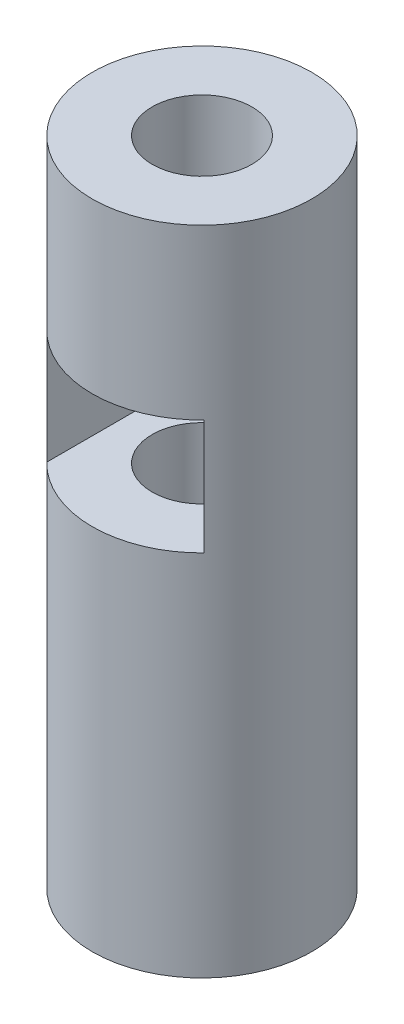
SolidWorks part; units mm, degrees
ref_plane "Front Plane" through (0, 0, 0) normal (0, 0, 1) x (1, 0, 0)
ref_plane "Top Plane" through (0, 0, 0) normal (0, 1, 0) x (1, 0, 0)
ref_plane "Right Plane" through (0, 0, 0) normal (1, 0, 0) x (0, 0, -1)
sketch "Sketch1" plane through (0, 0, 0) normal (0, 1, 0) x (1, 0, 0)
  circle A0 centre (0, 0) radius 3
  circle A1 centre (0, 0) radius 5.725
  dimension "D1" = 6
  dimension "D2" = 11.45
extrude "Boss-Extrude1" add sketch "Sketch1" along normal blind 34
ref_plane "Plane1" through (0, 7.2, 0) normal (0, 1, 0) x (1, 0, 0)
sketch "Sketch2" plane through (0, 0, 0) normal (0, -1, 0) x (-1, 0, 0)
  circle A0 centre (0, 0) radius 5.725
  dimension "D1" = 11.45
extrude "Boss-Extrude2" add sketch "Sketch2" against normal blind 34
sketch "Sketch3" plane through (0, 0, 0) normal (0, -1, 0) x (-1, 0, 0)
  circle A1 centre (0, 0) radius 2.6
  dimension "D1" = 5.2
extrude "Cut-Extrude1" cut sketch "Sketch3" against normal blind 40
sketch "Sketch4" plane through (0, 7.2, 0) normal (0, 1, 0) x (1, 0, 0)
  line L1 (0, -4.7343) -> (4.1, -2.3671)
  line L2 (4.1, -2.3671) -> (4.1, 2.3671)
  line L3 (4.1, 2.3671) -> (0, 4.7343)
  line L4 (0, 4.7343) -> (-4.1, 2.3671)
  line L5 (-4.1, 2.3671) -> (-4.1, -2.3671)
  line L6 (-4.1, -2.3671) -> (0, -4.7343)
  circle A0 centre (0, 0) radius 4.1 construction
  dimension "D1" = 8.2
extrude "Cut-Extrude2" cut sketch "Sketch4" against normal blind 4.7
sketch "Sketch5" plane through (0, 0, 0) normal (0, 0, 1) x (1, 0, 0)
  line L0 (0, -1.5413) -> (0, 31.7188) construction
  line L1 (6.2975, 7.2) -> (-6.2975, 7.2) construction
  line L2 (4.1, 2.5) -> (-4.1, 2.5)
  line L3 (4.1, 2.5) -> (4.1, 7.2)
  line L4 (4.1, 7.2) -> (-4.1, 7.2)
  line L5 (-4.1, 2.5) -> (-4.1, 7.2)
  line L6 (4.1, 2.5) -> (-4.1, 7.2) construction
  line L7 (4.1, 7.2) -> (-4.1, 2.5) construction
  line L9 (-5.725, 0) -> (5.725, 0) construction
  point P3 (0, 4.85)
  dimension "D1" = 0
  dimension "D3" = 8.2
  dimension "D4" = 2.5
extrude "Cut-Extrude3" cut sketch "Sketch5" against normal blind 10
ref_plane "Plane2" through (0, 19.2, 0) normal (0, 1, 0) x (1, 0, 0)
sketch "Sketch6" plane through (0, 19.2, 0) normal (0, 1, 0) x (1, 0, 0)
  line L2 (4.1, -2.3671) -> (4.1, 2.3671)
  line L3 (4.1, 2.3671) -> (0, 4.7343)
  line L4 (0, 4.7343) -> (-4.1, 2.3671)
  line L5 (-4.1, 2.3671) -> (-4.1, -6.0044)
  line L7 (4.1, 2.3671) -> (-4.1, 2.3671)
  line L12 (4.1, -2.3671) -> (4.1, -15.6595)
  line L13 (4.1, -15.6595) -> (-4.1, -15.6595)
  line L14 (-4.1, -6.0044) -> (-4.1, -15.6595)
  line L15 (0, -4.7343) -> (7.25, -0.5485) [skipped]
  line L16 (-4.1, -2.3671) -> (3.15, -6.5529) [skipped]
  circle A0 centre (0, 0) radius 7.25 construction
  dimension "D1" = 8.2
extrude "Cut-Extrude10" cut sketch "Sketch6" along normal blind 6 contours L5 L14 L13 L12 L2 L7 | L7 L3 L4
